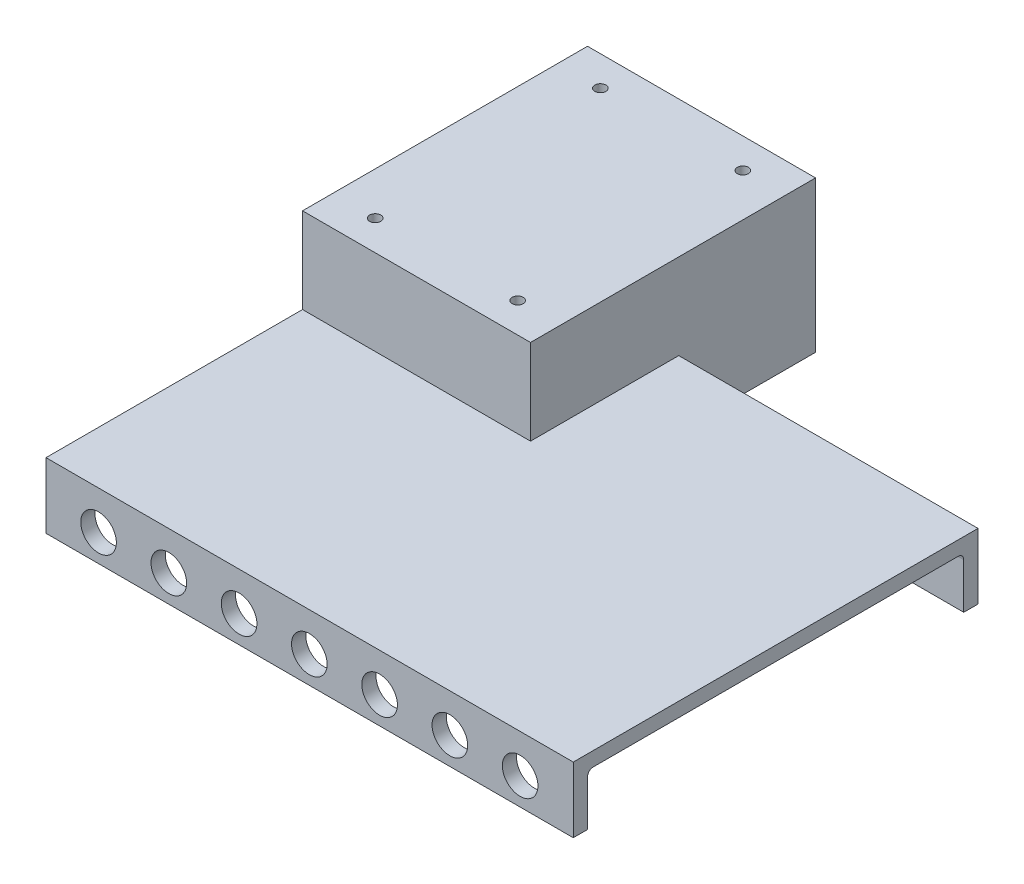
SolidWorks part; units mm, degrees
ref_plane "Front Plane" through (0, 0, 0) normal (0, 0, 1) x (1, 0, 0)
ref_plane "Top Plane" through (0, 0, 0) normal (0, 1, 0) x (1, 0, 0)
ref_plane "Right Plane" through (0, 0, 0) normal (1, 0, 0) x (0, 0, -1)
sketch "Sketch1" plane through (0, 0, 0) normal (0, 1, 0) x (1, 0, 0)
  line L1 (0, 0) -> (185, 0)
  line L2 (0, 0) -> (0, 142)
  line L3 (0, 142) -> (185, 142)
  line L4 (185, 0) -> (185, 142)
  point P5 (0, 0)
  dimension "D1" = 185
  dimension "D2" = 142
extrude "Boss-Extrude1" add sketch "Sketch1" along normal blind 23
sketch "Sketch12" plane through (0, 0, 0) normal (0, 1, 0) x (1, 0, 0)
  line L1 (0, 90) -> (80, 90)
  line L2 (0, 90) -> (0, 190)
  line L3 (0, 190) -> (80, 190)
  line L4 (80, 90) -> (80, 190)
  point P4 (0, 0)
  point P6 (0, 0)
  point P8 (0, 0)
  point P9 (0, 0)
  point P10 (0, 0)
  dimension "D1" = 90
  dimension "D2" = 80
  dimension "D3" = 100
extrude "Boss-Extrude6" add sketch "Sketch12" along normal blind 53
shell "Shell1" thickness 5
sketch "Sketch11" plane through (0, 0, 0) normal (0, 0, 1) x (1, 0, 0)
  line L0 (0, 23) -> (0, 0) construction
  line L3 (0, 23) -> (185, 23) construction
  circle A6 centre (18.4375, 9.5) radius 6.25
  circle A7 centre (43.0889, 9.5) radius 6.25
  circle A8 centre (67.7402, 9.5) radius 6.25
  circle A9 centre (92.3916, 9.5) radius 6.25
  circle A10 centre (117.0429, 9.5) radius 6.25
  circle A11 centre (141.6943, 9.5) radius 6.25
  circle A12 centre (166.3456, 9.5) radius 6.25
  point P20 (0, 0)
  point P21 (0, 0)
  point P22 (43.0889, 11.5)
  point P23 (0, 0)
  dimension "D1" = 12.5
  dimension "D2" = 18.4375
  dimension "D4" = 24.6514
  dimension "D5" = 13.5
  dimension "D3" = 7
extrude "Cut-Extrude2" cut sketch "Sketch11" against normal blind 6
fillet "Fillet1" radius 2 5 edges at (92.5, 18, -5) (130, 18, -137) (75, 48, -140) (37.5, 48, -95) (37.5, 48, -185)
sketch "Sketch13" plane through (0, 53, 0) normal (0, 1, 0) x (1, 0, 0)
  line L1 (0, 140) -> (80, 140) construction
  line L2 (0, 90) -> (0, 190) construction
  line L3 (80, 90) -> (80, 190) construction
  line L4 (40, 190) -> (40, 90) construction
  line L5 (0, 190) -> (80, 190) construction
  line L6 (0, 90) -> (80, 90) construction
  circle A0 centre (15, 100.5) radius 1.95
  circle A1 centre (15, 179.5) radius 1.95
  circle A2 centre (65, 179.5) radius 1.95
  circle A3 centre (65, 100.5) radius 1.95
  point P8 (0, 0)
  point P21 (0, 0)
  dimension "D1" = 3.9
  dimension "D2" = 79
  dimension "D3" = 50
extrude "Cut-Extrude3" cut sketch "Sketch13" against normal through all
